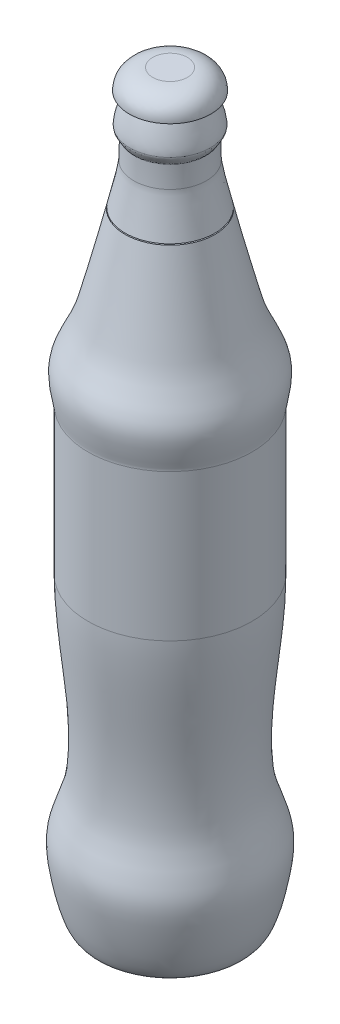
SolidWorks part; units mm, degrees
ref_plane "Plano frontal" through (0, 0, 0) normal (0, 0, 1) x (1, 0, 0)
ref_plane "Plano superior" through (0, 0, 0) normal (0, 1, 0) x (1, 0, 0)
ref_plane "Plano direito" through (0, 0, 0) normal (1, 0, 0) x (0, 0, -1)
sketch "Esboço2" plane through (0, 0, 0) normal (0, 0, 1) x (1, 0, 0)
  line L0 (0, 0) -> (0, 80) construction
  line L1 (-10, 80) -> (10, 80)
  line L2 (-10, 80) -> (-10, 0)
  line L3 (-10, 0) -> (10, 0)
  line L4 (10, 80) -> (10, 0)
  line L5 (-226.8219, 111.0719) -> (-26.8219, 111.0719) construction
  dimension "D1" = 20
  dimension "D2" = 80
sketch "Esboço3" plane through (0, 0, 0) normal (0, 0, 1) x (1, 0, 0)
  line L0 (61.6018, 32.4021) -> (61.6018, 47.8386)
  line L4 (66.4764, 70.3449) -> (66.4764, 74.4591) construction
  line L7 (65.9996, 73.3703) -> (70.2369, 73.3703) construction
  line L9 (65.9493, 76.4714) -> (70.2369, 76.4714) construction
  line L10 (66.4764, 71.6551) -> (66.4764, 72.6387) construction
  line L11 (65.9996, 72.8706) -> (65.9996, 73.87) construction
  line L12 (65.9996, 74.64) -> (65.9996, 72.0995) construction
  line L13 (69.3157, 78.5883) -> (71.3057, 78.5883) construction
  line L14 (65.9493, 75.8068) -> (65.9493, 77.0589) construction
  line L15 (68.4095, 78.5883) -> (70.2369, 78.5883)
  line L16 (79.7348, 41.0622) -> (60.7391, 41.0622) construction
  line L18 (70.2369, 41.0622) -> (70.2369, -7.8367) construction
  line L20 (65.9493, 76.4714) -> (66.8395, 76.4714)
  line L22 (63.0495, 0.7286) -> (70.2369, 0.7286)
  line L23 (70.2369, 0.7286) -> (70.2369, 78.5883)
  line L24 (61.6018, 36.7371) -> (61.6018, 28.0671) construction
  line L25 (62.8115, 0.7286) -> (64.1507, 0.7286) construction
  line L26 (66.5147, 72.127) -> (66.322, 68.1468) construction
  line L27 (61.6018, 48.115) -> (61.6018, 47.5621) construction
  spline S0 degree 3 poles (63.0495, 0.7286) (62.2805, 0.7286) (61.1949, 5.3494) (60.8382, 9.371) (62.3335, 12.3881) (63.1797, 20.2486) (61.6018, 26.9833) (61.6018, 32.4021) knots 0 0 0 0 0.184554 0.267801 0.401844 0.475322 1 1 1 1
  spline S1 degree 3 poles (61.6018, 47.8386) (61.6018, 48.1568) (60.8599, 50.8213) (61.7729, 53.2403) (62.7835, 55.0897) (63.8742, 58.8856) (66.3693, 69.1226) (66.4193, 70.1558) knots 0 0 0 0 0.18693 0.313358 0.493596 0.56226 1 1 1 1
  spline S3 degree 3 poles (66.4764, 72.402) (66.4764, 71.6981) (66.4572, 70.9388) (66.4193, 70.1558) knots 0 0 0 0 0.075054 0.075054 0.075054 0.075054
  spline S5 degree 3 poles (65.9996, 73.3703) (65.9996, 73.0591) (66.4764, 72.5293) (66.4764, 72.402) knots 0 0 0 0 1 1 1 1
  spline S6 degree 2 poles (65.9996, 73.3703) (65.9996, 74.1971) (66.8395, 76.4714) knots 0 0 0 1 1 1
  spline S7 degree 3 poles (68.4095, 78.5883) (67.1553, 78.5883) (65.9493, 77.852) (65.9493, 76.4714) knots 0 0 0 0 1 1 1 1
  point P20 (63.0495, 0.7286)
revolve "Revolução1" add sketch "Esboço3" angle 360 about L23
ref_plane "Plano1" through (0, 65.7286, 0) normal (0, -1, 0) x (-1, 0, 0)
sketch "Esboço4" plane through (0, 65.7286, 0) normal (0, -1, 0) x (-1, 0, 0)
  circle A0 centre (-70.2369, 0) radius 12.0214
extrude "Corte-extrusão1" cut sketch "Esboço4" against normal blind 0.1
sketch "Esboço5" plane through (0, 0.7286, 0) normal (0, -1, 0) x (1, 0, 0)
  circle A0 centre (70.2369, 0) radius 0.5
  dimension "D1" = 1
extrude "Corte-extrusão2" cut sketch "Esboço5" against normal blind 0.4
